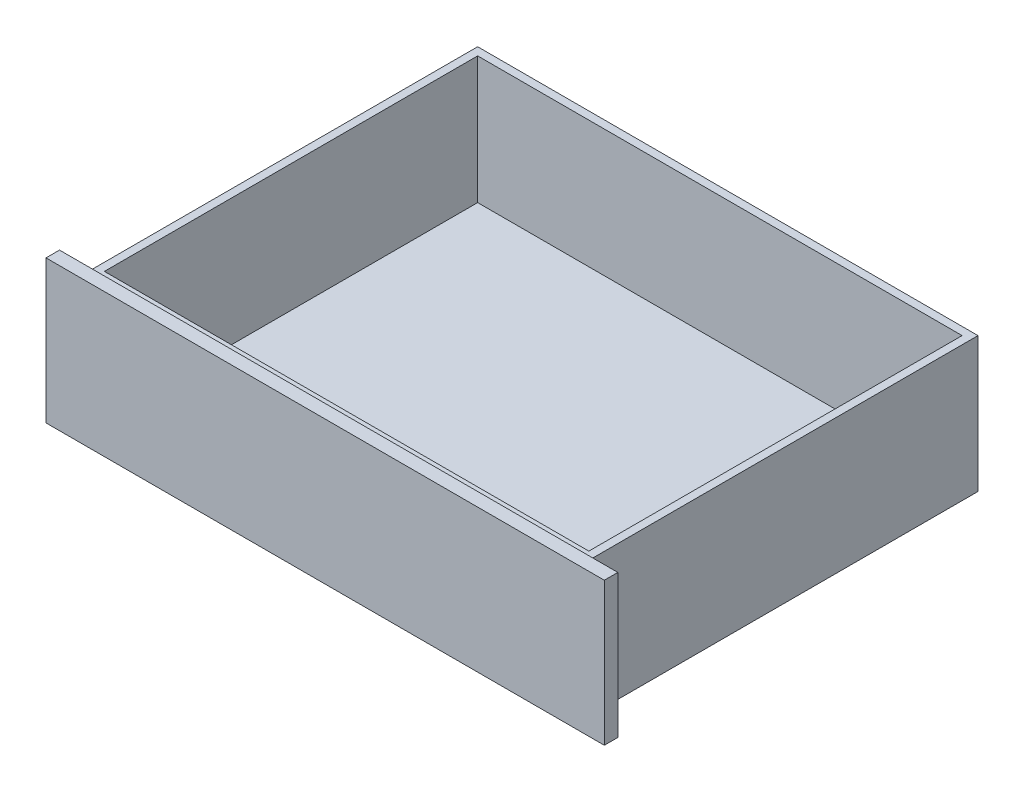
SolidWorks part; units mm, degrees
material "Maple"
ref_plane "Front Plane" through (0, 0, 0) normal (0, 0, 1) x (1, 0, 0)
ref_plane "Top Plane" through (0, 0, 0) normal (0, 1, 0) x (1, 0, 0)
ref_plane "Right Plane" through (0, 0, 0) normal (1, 0, 0) x (0, 0, -1)
sketch "Sketch1" plane through (0, 0, 0) normal (0, 1, 0) x (1, 0, 0)
  line L1 (-315, -245) -> (315, -245)
  line L2 (-315, -245) -> (-315, 245)
  line L3 (-315, 245) -> (315, 245)
  line L4 (315, -245) -> (315, 245)
  line L5 (-315, -245) -> (315, 245) construction
  line L6 (-315, 245) -> (315, -245) construction
  point P0 (0, 0)
  dimension "D1" = 630
  dimension "D2" = 490
extrude "Extrusion" add sketch "Sketch1" along normal blind 170
shell "Drawer's interior" thickness 10
sketch "Sketch2" plane through (0, 0, 245) normal (0, 0, 1) x (1, 0, 0)
  line L0 (-315, 0) -> (315, 0) construction
  line L1 (-351.5, -5) -> (351.5, -5)
  line L2 (-351.5, -5) -> (-351.5, 175)
  line L3 (-351.5, 175) -> (351.5, 175)
  line L4 (351.5, -5) -> (351.5, 175)
  line L5 (-351.5, -5) -> (351.5, 175) construction
  line L6 (-351.5, 175) -> (351.5, -5) construction
  line L7 (315, 170) -> (315, 0) construction
  point P0 (0, 85)
  point P8 (0, 0)
  point P14 (315, 85)
  dimension "D1" = 703
  dimension "D2" = 180
extrude "Boss-Extrude2" add sketch "Sketch2" along normal blind 17 contours L4 L3 L2 L1
